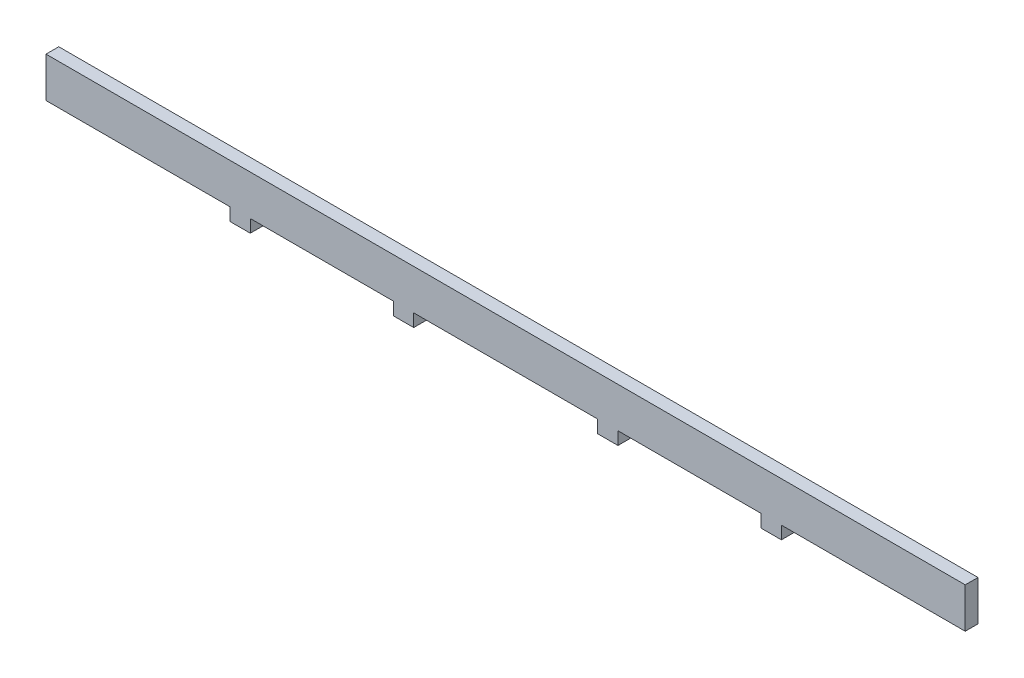
SolidWorks part; units mm, degrees
ref_plane "Front Plane" through (0, 0, 0) normal (0, 0, 1) x (1, 0, 0)
ref_plane "Top Plane" through (0, 0, 0) normal (0, 1, 0) x (1, 0, 0)
ref_plane "Right Plane" through (0, 0, 0) normal (1, 0, 0) x (0, 0, -1)
sketch "Sketch1" plane through (0, 0, 0) normal (0, 0, 1) x (1, 0, 0)
  line L0 (-2.2672, 60.1068) -> (-2.2672, 56.9318)
  line L1 (-139.4272, 70.1068) -> (89.1728, 70.1068)
  line L2 (-139.4272, 70.1068) -> (-139.4272, 60.1068)
  line L3 (-139.4272, 60.1068) -> (-93.7072, 60.1068)
  line L4 (89.1728, 70.1068) -> (89.1728, 60.1068)
  line L5 (-47.9872, 60.1068) -> (-2.2672, 60.1068)
  line L6 (-93.7072, 60.1068) -> (-93.7072, 56.9318)
  line L7 (-93.7072, 56.9318) -> (-88.6272, 56.9318)
  line L8 (-88.6272, 60.1068) -> (-88.6272, 56.9318)
  line L9 (2.8128, 60.1068) -> (38.3728, 60.1068)
  line L10 (-53.0672, 60.1068) -> (-53.0672, 56.9318)
  line L11 (-53.0672, 56.9318) -> (-47.9872, 56.9318)
  line L12 (-47.9872, 60.1068) -> (-47.9872, 56.9318)
  line L13 (-2.2672, 56.9318) -> (2.8128, 56.9318)
  line L14 (2.8128, 60.1068) -> (2.8128, 56.9318)
  line L15 (38.3728, 60.1068) -> (38.3728, 56.9318)
  line L16 (38.3728, 56.9318) -> (43.4528, 56.9318)
  line L17 (43.4528, 60.1068) -> (43.4528, 56.9318)
  line L18 (-88.6272, 60.1068) -> (-53.0672, 60.1068)
  line L19 (43.4528, 60.1068) -> (89.1728, 60.1068)
  dimension "D1" = 228.6
  dimension "D2" = 10
  dimension "D3" = 45.72
  dimension "D4" = 5.08
  dimension "D5" = 3.175
  dimension "D6" = 35.56
  dimension "D7" = 5.08
  dimension "D8" = 3.175
extrude "Boss-Extrude1" add sketch "Sketch1" along normal blind 3.175
